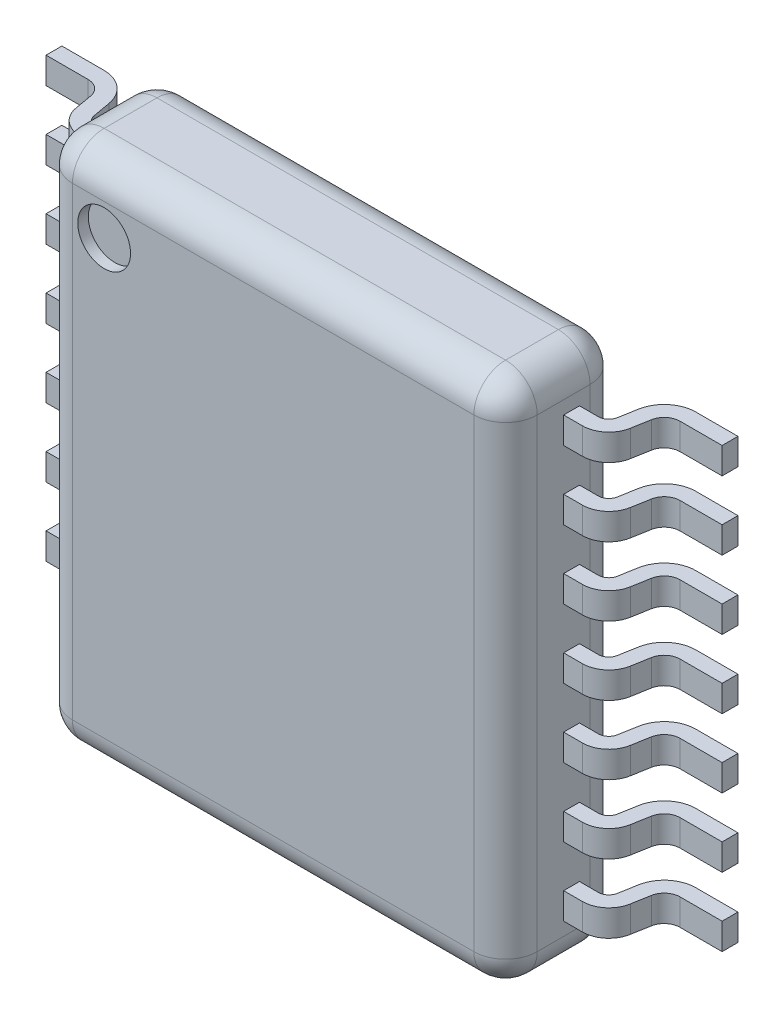
SolidWorks part; units mm, degrees
ref_plane "Plan de face" through (0, 0, 0) normal (0, 0, 1) x (1, 0, 0)
ref_plane "Plan de dessus" through (0, 0, 0) normal (0, 1, 0) x (1, 0, 0)
ref_plane "Plan de droite" through (0, 0, 0) normal (1, 0, 0) x (0, 0, -1)
sketch "Sketch1" plane through (0, 0, 0) normal (0, 0, 1) x (1, 0, 0)
  line L1 (-2.2, 2.5) -> (2.2, 2.5)
  line L2 (-2.2, 2.5) -> (-2.2, -2.5)
  line L3 (-2.2, -2.5) -> (2.2, -2.5)
  line L4 (2.2, 2.5) -> (2.2, -2.5)
  line L5 (-2.2, 2.5) -> (2.2, -2.5) construction
  line L6 (-2.2, -2.5) -> (2.2, 2.5) construction
  point P0 (0, 0)
  dimension "D1" = 5
  dimension "D2" = 4.4
extrude "Boss-Extrude1" add sketch "Sketch1" along normal offset from surface (1.1 mm away) 1.2 from offset 0.1 up to plane "Plan de face"
fillet "Fillet1" radius 0.3 12 edges at (0, 2.5, 0.1) (0, 2.5, 1.2) (2.2, 2.5, 0.65) (2.2, 0, 0.1) (2.2, 0, 1.2) (2.2, -2.5, 0.65) (0, -2.5, 0.1) (0, -2.5, 1.2) (-2.2, -2.5, 0.65) (-2.2, 0, 0.1) (-2.2, 2.5, 0.65) (-2.2, 0, 1.2)
sketch "Sketch2" plane through (0, 0, 1.2) normal (0, 0, 1) x (1, 0, 0)
  circle A0 centre (-1.6, 1.9) radius 0.25
  dimension "D1" = 0.5
  dimension "D2" = 1.9
  dimension "D3" = 1.6
extrude "Cut-Extrude1" cut sketch "Sketch2" against normal blind 0.1
sketch "Sketch3" plane through (0, 0, 0) normal (0, 1, 0) x (1, 0, 0)
  line L0 (-3.2, 0) -> (-2.8017, 0)
  line L1 (-2.5063, -0.2479) -> (-2.4764, -0.4174)
  line L2 (-2.3779, -0.5) -> (-2.2, -0.5)
  line L3 (-2.2, -1.2) -> (-2.2, -0.1) construction
  line L4 (-2.2, -0.1) -> (2.2, -0.1) construction
  line L5 (-3.2, -0.15) -> (-2.8017, -0.15)
  line L6 (-2.654, -0.274) -> (-2.6241, -0.4434)
  line L7 (-2.3779, -0.65) -> (-2.2, -0.65)
  line L8 (-3.2, -0.15) -> (-3.2, 0)
  line L9 (-2.2, -0.65) -> (-2.2, -0.5)
  arc A0 (-2.8017, 0) -> (-2.5063, -0.2479) centre (-2.8017, -0.3) cw
  arc A1 (-2.4764, -0.4174) -> (-2.3779, -0.5) centre (-2.3779, -0.4) ccw
  arc A2 (-2.8017, -0.15) -> (-2.654, -0.274) centre (-2.8017, -0.3) cw
  arc A3 (-2.6241, -0.4434) -> (-2.3779, -0.65) centre (-2.3779, -0.4) ccw
  point P12 (-2.55, 0)
  dimension "D5" = 0.3
  dimension "D6" = 0.1
  dimension "D1" = 0.65
  dimension "D2" = 3.2
  dimension "D3" = 100
  dimension "D4" = 0.4
  dimension "D7" = 0.15
extrude "Boss-Extrude2" add sketch "Sketch3" along normal mid plane 0.25 from offset 1.95
pattern_linear "LPattern1" count 7 spacing 0.65 along (0, -1, 0) of "Boss-Extrude2"
mirror "Mirror1" about plane through (0, 0, 0) normal (1, 0, 0) of "LPattern1", "Boss-Extrude2"
sketch "Sketch4" plane through (0, 0, 0.1) normal (0, 0, -1) x (-1, 0, 0)
  line L1 (-0.825, 0.675) -> (0.825, 0.675)
  line L2 (-0.825, 0.675) -> (-0.825, -0.675)
  line L3 (-0.825, -0.675) -> (0.825, -0.675)
  line L4 (0.825, 0.675) -> (0.825, -0.675)
  line L5 (-0.825, 0.675) -> (0.825, -0.675) construction
  line L6 (-0.825, -0.675) -> (0.825, 0.675) construction
  point P0 (0, 0)
  dimension "D1" = 1.35
  dimension "D2" = 1.65
extrude "Cut-Extrude2" cut sketch "Sketch4" against normal blind 0.01
equation "\"D19@Boss-Extrude2\"=0.65*3"
